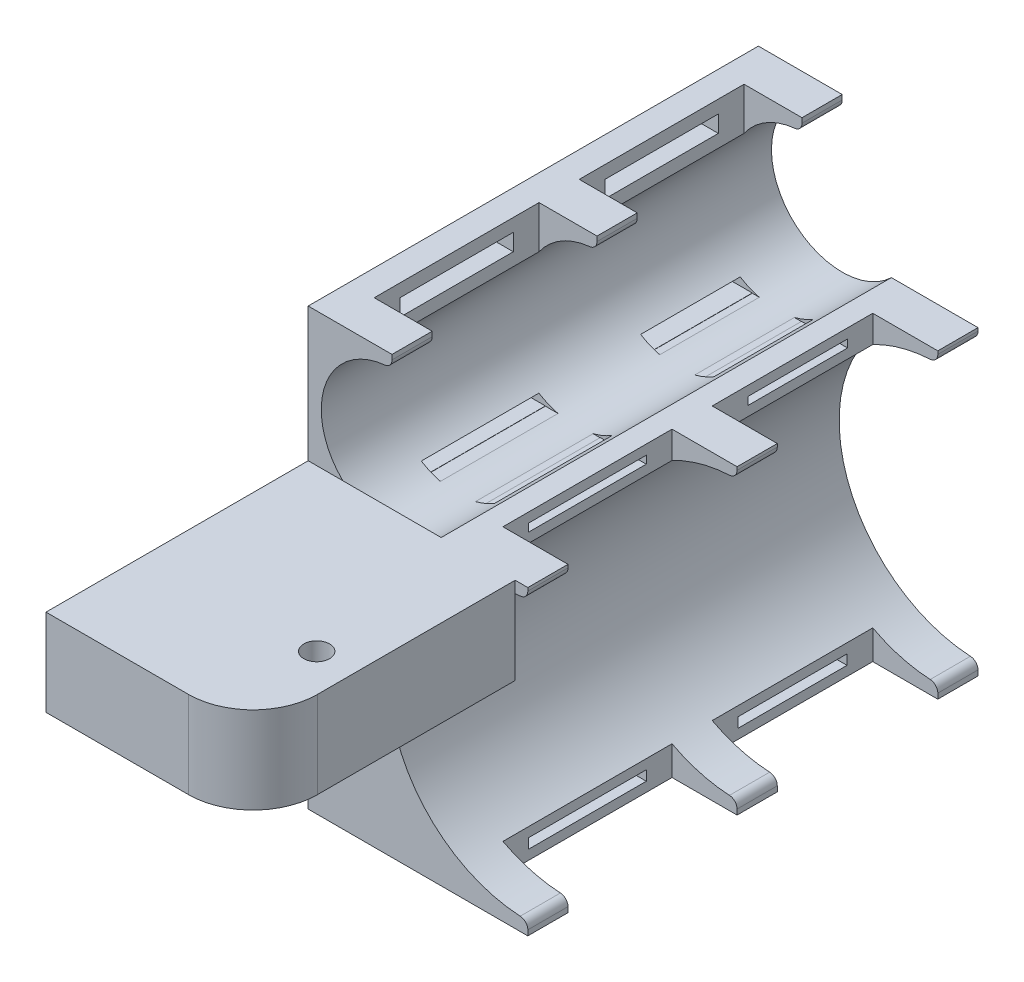
SolidWorks part; units mm, degrees
ref_plane "Front Plane" through (0, 0, 0) normal (0, 0, 1) x (1, 0, 0)
ref_plane "Top Plane" through (0, 0, 0) normal (0, 1, 0) x (1, 0, 0)
ref_plane "Right Plane" through (0, 0, 0) normal (1, 0, 0) x (0, 0, -1)
sketch "Sketch1" plane through (0, 0, 0) normal (0, 0, 1) x (1, 0, 0)
  line L3 (22.4738, 84.758) -> (22.4738, 83.0587)
  line L4 (22.4738, 39.8787) -> (22.4738, 37.8467)
  line L5 (22.4738, 37.8467) -> (-11.6734, 37.8467)
  line L6 (-11.6734, 37.8467) -> (-11.6734, 105.594)
  line L7 (-11.6734, 105.594) -> (1.3586, 105.594)
  line L9 (1.3586, 105.594) -> (1.3586, 103.6651)
  line L10 (22.4738, 84.758) -> (9.0057, 84.758)
  circle A0 centre (1.3586, 92.6651) radius 11 construction
  circle A1 centre (22.4738, 61.4687) radius 21.59 construction
  arc A2 (1.3586, 103.6651) -> (9.0057, 84.758) centre (1.3586, 92.6651) ccw
  arc A3 (22.4738, 83.0587) -> (22.4738, 39.8787) centre (22.4738, 61.4687) ccw
  dimension "D1" = 2.032
extrude "Boss-Extrude1" add sketch "Sketch1" against normal blind 70
sketch "Sketch2" plane through (0, 105.594, 0) normal (0, 1, 0) x (1, 0, 0)
  line L0 (22.4738, 70) -> (22.4738, 0) construction
  line L1 (-7.6541, 63.75) -> (22.4738, 63.75)
  line L2 (-7.6541, 63.75) -> (-7.6541, 38.125)
  line L3 (-7.6541, 6.25) -> (22.4738, 6.25)
  line L4 (22.4738, 63.75) -> (22.4738, 38.125)
  line L5 (-7.6541, 38.125) -> (22.4738, 38.125)
  line L7 (22.4738, 31.875) -> (-7.6541, 31.875)
  line L8 (22.4738, 31.875) -> (22.4738, 6.25)
  line L9 (-7.6541, 31.875) -> (-7.6541, 6.25)
  line L10 (9.0057, 70) -> (-9.6414, 70) construction
  line L11 (-9.6414, 0) -> (9.0057, 0) construction
  dimension "D1" = 6.25
  dimension "D2" = 6.25
  dimension "D3" = 6.25
extrude "Cut-Extrude1" cut sketch "Sketch2" against normal blind 10
sketch "Sketch3" plane through (0, 84.758, 0) normal (0, 1, 0) x (1, 0, 0)
  line L0 (12.3586, 0.5606) -> (12.3586, 68.5606) construction
  line L5 (12.3586, 63.75) -> (48.4941, 63.75)
  line L6 (12.3586, 63.75) -> (12.3586, 38.7891)
  line L7 (12.3586, 6.25) -> (48.4941, 6.25)
  line L8 (48.4941, 63.75) -> (48.4941, 38.7891)
  line L9 (22.4738, 0) -> (9.0057, 0) construction
  line L10 (22.4738, 70) -> (9.0057, 70) construction
  line L11 (12.3586, 38.7891) -> (48.4941, 38.7891)
  line L13 (48.4941, 32.5391) -> (12.3586, 32.5391)
  line L14 (12.3586, 32.5391) -> (12.3586, 6.25)
  line L15 (48.4941, 32.5391) -> (48.4941, 6.25)
  point P14 (15.7398, 70)
  dimension "D1" = 6.25
  dimension "D2" = 6.25
  dimension "D3" = 6.25
extrude "Cut-Extrude2" cut sketch "Sketch3" against normal through all
sketch "Sketch5" plane through (-11.6734, 0, 0) normal (-1, 0, 0) x (0, 0, 1)
  line L0 (40.7692, 62.2625) -> (40.7692, 81.4327) construction
  line L1 (0, 84.758) -> (40.7692, 84.758)
  line L2 (0, 84.758) -> (0, 71.258)
  line L3 (0, 71.258) -> (40.7692, 71.258)
  line L4 (40.7692, 84.758) -> (40.7692, 71.258)
  dimension "D1" = 13.5
extrude "Boss-Extrude2" add sketch "Sketch5" against normal blind 50
sketch "Sketch6" plane through (0, 84.758, 0) normal (0, 1, 0) x (1, 0, 0)
  circle A0 centre (14.6476, -25) radius 2
  circle A1 centre (30.3294, -25) radius 2
  dimension "D1" = 4
  dimension "D2" = 4
extrude "Cut-Extrude3" cut sketch "Sketch6" against normal blind 50
fillet "Fillet1" radius 1.25 9 edges at (22.4738, 39.8787, -66.875) (22.4738, 39.8787, -35.6641) (22.4738, 39.8787, -3.125) (22.4738, 83.0587, -3.125) (22.4738, 83.0587, -35.6641) (22.4738, 83.0587, -66.875) (1.3586, 103.6651, -66.875) (1.3586, 103.6651, -35) (1.3586, 103.6651, -3.125)
fillet "Fillet2" radius 16 2 edges at (38.3266, 78.008, 0) (38.3266, 78.008, 40.7692)
sketch "Sketch7" plane through (0, 84.758, 0) normal (0, 1, 0) x (1, 0, 0)
  line L0 (22.3266, -40.7692) -> (-11.6734, -40.7692) construction
  line L1 (20.508, -40.7692) -> (40.3136, -40.7692)
  line L2 (20.508, -40.7692) -> (20.508, 0)
  line L3 (20.508, 0) -> (40.3136, 0)
  line L4 (40.3136, -40.7692) -> (40.3136, 0)
extrude "Cut-Extrude4" cut sketch "Sketch7" against normal through all
fillet "Fillet3" radius 10 1 edges at (20.508, 78.008, 40.7692)
sketch "Sketch9" plane through (12.3586, 0, 0) normal (1, 0, 0) x (0, 0, -1)
  line L0 (63.75, 105.594) -> (38.125, 105.594) construction
  line L1 (59.835, 83.258) -> (44.3583, 83.258)
  line L2 (59.835, 83.258) -> (59.835, 82.0426)
  line L3 (59.835, 82.0426) -> (44.3583, 82.0426)
  line L4 (44.3583, 83.258) -> (44.3583, 82.0426)
  line L5 (28.5391, 83.258) -> (10.25, 83.258)
  line L6 (28.5391, 83.258) -> (28.5391, 82.0426)
  line L7 (28.5391, 82.0426) -> (10.25, 82.0426)
  line L8 (10.25, 83.258) -> (10.25, 82.0426)
  line L9 (59.75, 103.594) -> (42.125, 103.594)
  line L10 (59.75, 103.594) -> (59.75, 100.9715)
  line L11 (59.75, 100.9715) -> (42.125, 100.9715)
  line L12 (42.125, 103.594) -> (42.125, 100.9715)
  line L13 (27.875, 103.594) -> (10.25, 103.594)
  line L14 (27.875, 103.594) -> (27.875, 100.9715)
  line L15 (27.875, 100.9715) -> (10.25, 100.9715)
  line L16 (10.25, 103.594) -> (10.25, 100.9715)
  line L17 (38.125, 98.9715) -> (63.75, 98.9715) construction
  line L18 (31.875, 105.594) -> (6.25, 105.594) construction
  line L19 (6.25, 98.9715) -> (31.875, 98.9715) construction
  line L20 (38.7891, 80.5426) -> (63.75, 80.5426) construction
  line L22 (63.75, 84.758) -> (38.7891, 84.758) construction
  line L23 (70, 84.758) -> (0, 84.758) construction
  line L24 (6.25, 80.5426) -> (32.5391, 80.5426) construction
  line L25 (32.5391, 80.5426) -> (32.5391, 84.758) construction
  line L26 (6.25, 80.5426) -> (6.25, 84.758) construction
  line L27 (6.25, 98.9715) -> (6.25, 103.6077) construction
  line L28 (31.875, 103.6077) -> (31.875, 98.9715) construction
  line L29 (38.125, 98.9715) -> (38.125, 105.594) construction
  line L30 (63.75, 98.9715) -> (63.75, 105.594) construction
  line L31 (63.75, 42.3949) -> (38.7891, 42.3949) construction
  line L32 (59.75, 40.8949) -> (42.7891, 40.8949)
  line L33 (59.75, 40.8949) -> (59.75, 39.3467)
  line L34 (59.75, 39.3467) -> (42.7891, 39.3467)
  line L35 (42.7891, 40.8949) -> (42.7891, 39.3467)
  line L36 (28.5391, 40.8949) -> (10.25, 40.8949)
  line L37 (28.5391, 40.8949) -> (28.5391, 39.3467)
  line L38 (28.5391, 39.3467) -> (10.25, 39.3467)
  line L39 (10.25, 40.8949) -> (10.25, 39.3467)
  line L40 (63.75, 37.8467) -> (38.7891, 37.8467) construction
  line L41 (32.5391, 37.8467) -> (6.25, 37.8467) construction
  line L42 (32.5391, 42.3949) -> (6.25, 42.3949) construction
  line L43 (63.75, 37.8467) -> (63.75, 42.3949) construction
  line L44 (38.7891, 37.8467) -> (38.7891, 42.3949) construction
  line L45 (6.25, 37.8467) -> (6.25, 42.3949) construction
  point P32 (28.5391, 82.6503)
  point P39 (27.875, 102.2828)
  dimension "D1" = 2
  dimension "D2" = 2
  dimension "D3" = 2
  dimension "D4" = 2
  dimension "D5" = 1.5
  dimension "D6" = 1.5
  dimension "D7" = 1.5
  dimension "D8" = 1.5
  dimension "D9" = 4
  dimension "D10" = 4
  dimension "D11" = 4
  dimension "D12" = 4
  dimension "D13" = 4
  dimension "D14" = 4
  dimension "D15" = 1.5
  dimension "D16" = 1.5
  dimension "D17" = 1.5
  dimension "D18" = 1.5
  dimension "D19" = 4
  dimension "D20" = 4
  dimension "D21" = 4
  dimension "D22" = 4
extrude "Cut-Extrude5" cut sketch "Sketch9" against normal through all
sketch "Sketch10" plane through (0, 84.758, 0) normal (0, 1, 0) x (1, 0, 0)
  line L0 (4.2155, 59.835) -> (12.3586, 59.835) construction
  line L1 (5.1958, 59.835) -> (-2.4564, 59.835)
  line L2 (5.1958, 59.835) -> (5.1958, 44.3583)
  line L3 (5.1958, 44.3583) -> (-2.4564, 44.3583)
  line L4 (-2.4564, 59.835) -> (-2.4564, 44.3583)
  line L5 (-1.4982, 44.3583) -> (-4.3428, 44.3583) construction
  line L6 (4.2155, 28.5391) -> (12.3586, 28.5391) construction
  line L7 (5.1958, 28.5391) -> (-3.3326, 28.5391)
  line L8 (5.1958, 28.5391) -> (5.1958, 10.25)
  line L9 (5.1958, 10.25) -> (-3.3326, 10.25)
  line L10 (-3.3326, 28.5391) -> (-3.3326, 10.25)
  line L11 (-1.4982, 10.25) -> (-4.3428, 10.25) construction
extrude "Cut-Extrude8" cut sketch "Sketch10" against normal blind 2.75
